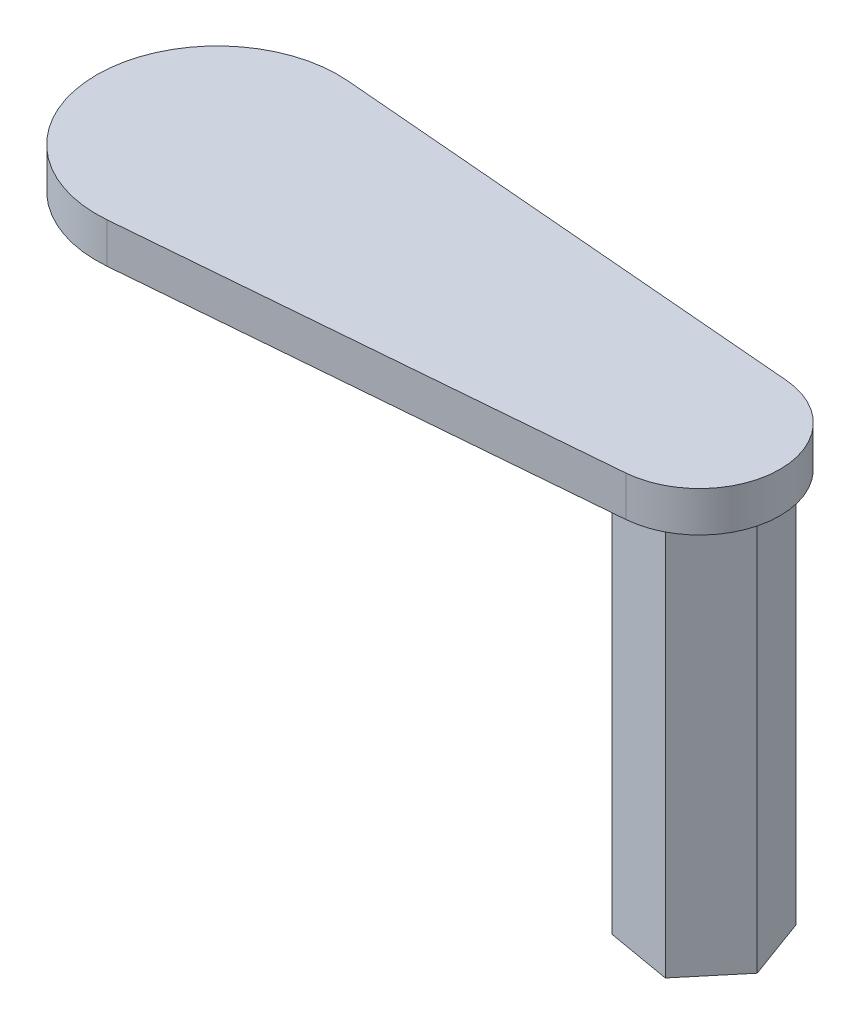
SolidWorks part; units mm, degrees
ref_plane "前视基准面" through (0, 0, 0) normal (0, 0, 1) x (1, 0, 0)
ref_plane "上视基准面" through (0, 0, 0) normal (0, 1, 0) x (1, 0, 0)
ref_plane "右视基准面" through (0, 0, 0) normal (1, 0, 0) x (0, 0, -1)
sketch "草图1" plane through (0, 0, 0) normal (0, 1, 0) x (1, 0, 0)
  line L1 (1.2528, 14.9476) -> (60.6994, 9.9651)
  line L2 (1.2528, -14.9476) -> (60.6994, -9.9651)
  circle A0 centre (0, 0) radius 15
  circle A2 centre (0, 0) radius 8.5
  circle A3 centre (59.8642, 0) radius 10
  dimension "D1" = 30
  dimension "D2" = 20
  dimension "D3" = 17
extrude "凸台-拉伸5" add sketch "草图1" along normal blind 5 contours A0 A2 | A3 L1 A0 L2 | A3 A0
sketch "草图3" plane through (0, 5, 0) normal (0, 1, 0) x (1, 0, 0)
  circle A0 centre (0, 0) radius 8.5
extrude "凸台-拉伸6" add sketch "草图3" against normal blind 3
sketch "草图4" plane through (0, 0, 0) normal (0, -1, 0) x (-1, 0, 0)
  line L1 (-64.1613, 5.2755) -> (-54.1613, 5.2755)
  line L2 (-64.1613, 5.2755) -> (-64.1613, -4.7245)
  line L3 (-64.1613, -4.7245) -> (-54.1613, -4.7245)
  line L4 (-54.1613, 5.2755) -> (-54.1613, -4.7245)
  line L5 (-64.1613, 5.2755) -> (-54.1613, -4.7245) construction
  line L6 (-64.1613, -4.7245) -> (-54.1613, 5.2755) construction
  line L7 (-51.6817, 2.1623) -> (-56.8721, 8.381)
  line L8 (-56.8721, 8.381) -> (-64.8529, 6.9954)
  line L9 (-64.8529, 6.9954) -> (-67.6433, -0.609)
  line L10 (-67.6433, -0.609) -> (-62.453, -6.8277)
  line L11 (-62.453, -6.8277) -> (-54.4722, -5.4421)
  line L12 (-54.4722, -5.4421) -> (-51.6817, 2.1623)
  circle A0 centre (-59.6625, 0.7767) radius 7.015 construction
  point P0 (-59.1613, 0.2755)
  dimension "D1" = 10
  dimension "D2" = 10
  dimension "D3" = 10
extrude "凸台-拉伸8" add sketch "草图4" along normal blind 50 contours L11 L12 L3 L2 L1 L7 L8 L9 L10 | L4 L12 L7 | L3 L12 L4 L7 L1 L2
